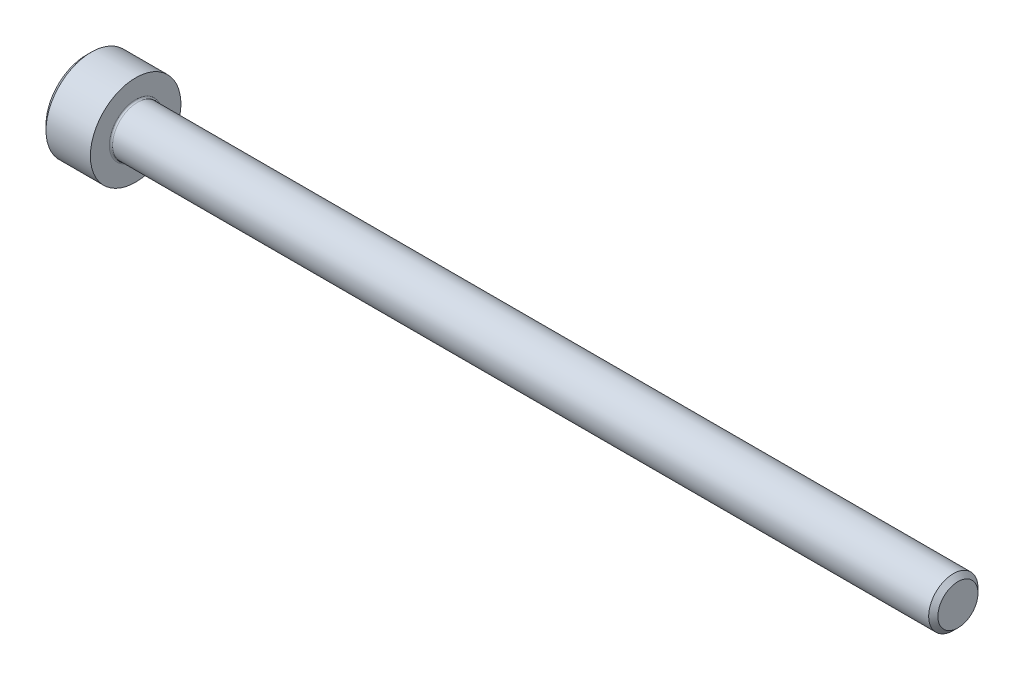
SolidWorks part; units mm, degrees
revolve "Base-Revolve" add sketch "BodySke"
sketch "BodySke" plane through (0, 0, 0) normal (0, 0, 1) x (1, 0, 0)
  line L0 (0, 0) -> (0, 2.45)
  line L1 (0.3, 2.75) -> (3, 2.75)
  line L2 (3, 2.75) -> (3, 1.5)
  line L3 (3, 1.5) -> (52.7195, 1.5)
  line L4 (53, 1.2195) -> (53, 0)
  line L5 (53, 0) -> (0, 0)
  line L6 (-31.75, 0) -> (127, 0) construction
  line L7 (0, 2.45) -> (0.3, 2.75)
  line L8 (53, 1.2195) -> (52.7195, 1.5)
  line L9 (0, -2.45) -> (0.3, -2.75) construction
  line L10 (53, -1.2195) -> (52.7195, -1.5) construction
  line L11 (3.5, 9.525) -> (3.5, 3.175) construction
  line L12 (35, 9.525) -> (35, 3.175) construction
  line L13 (3, 9.525) -> (3, 3.175) construction
  dimension "Diameter" = 3
  dimension "Head_ht" = 3
  dimension "Length" = 50
  dimension "Body_ch_ang" = 45
  dimension "Head_dia" = 5.5
  dimension "Head_ch_ang" = 45
  dimension "Minor_dia" = 2.439
  dimension "Advance" = 0.5
  dimension "Thread_nom" = 18
  dimension "Thread_length" = 50
  dimension "Head_ch_ht" = 0.3
cosmetic thread "ThreadCosmetic" [suppressed]
fillet "Fillet1" radius 0.1 1 edges at (3, 0, 1.5)
ref_plane "Plane1" through (0, 0, 0) normal (0, 0, 1) x (1, 0, 0)
ref_plane "Plane2" through (0, 0, 0) normal (0, 1, 0) x (1, 0, 0)
ref_plane "Plane3" through (0, 0, 0) normal (1, 0, 0) x (0, 0, -1)
sketch "Sketch2" plane through (0, 0, 0) normal (0, 0, 1) x (1, 0, 0)
  line L0 (0, 1.28) -> (1.3, 1.28)
  line L1 (1.3, 1.28) -> (2.039, 0)
  line L2 (-31.75, 0) -> (127, 0) construction
  line L3 (2.039, 0) -> (0, 0)
  line L4 (0, 0) -> (0, 1.28)
  line L5 (0, 2.45) -> (0, -2.45) construction
  line L6 (0, 0) -> (47.625, 0) construction
  line L7 (3, -2.75) -> (3, 2.75) construction
  dimension "D1" = 1.28
  dimension "D2" = 60
revolve "Hex-PreBroach" cut sketch "Sketch2" angle 360 about L6
sketch "Sketch3" plane through (0, 0, 0) normal (-1, 0, 0) x (0, 0.5, 0.866)
  line L0 (0.739, 1.28) -> (-0.739, 1.28)
  line L1 (-0.739, 1.28) -> (-1.478, 0)
  line L2 (0.739, 1.28) -> (1.478, 0)
  line L3 (0.739, -1.28) -> (1.478, 0)
  line L4 (0.739, -1.28) -> (-0.739, -1.28)
  line L5 (-0.739, -1.28) -> (-1.478, 0)
  dimension "D1" = 1.28
  dimension "D2" = 1.28
  dimension "Hex_size" = 2.56
extrude "Hex" cut sketch "Sketch3" against normal blind 1.3
sketch "Sketch4" plane through (0, 0, 0) normal (-1, 0, 0) x (0, 0, 1)
  line L0 (0, 0) -> (1.4605, 0)
  line L1 (0, 0) -> (6.1484, 3.5498) construction
  line L2 (0, 0) -> (0.7302, 1.2648)
  line L3 (1.2009, 0.3267) -> (1.3933, 0.4378)
  line L4 (0.8834, 0.8767) -> (1.0758, 0.9877)
  arc A0 (1.2009, 0.3267) -> (0.8834, 0.8767) centre (0, 0) ccw
  arc A1 (1.4605, 0) -> (1.3933, 0.4378) centre (0, 0) ccw
  arc A2 (0.7302, 1.2648) -> (1.0758, 0.9877) centre (0, 0) cw
  dimension "D1" = 30
  dimension "D2" = 60
  dimension "Spline_p_dim" = 0.635
  dimension "D3" = 0.3175
extrude "Spline" [suppressed] cut sketch "Sketch4" against normal blind 1.3
pattern_circular "CirPattern1" [suppressed] count 6 every 60
sketch "Sketch5" plane through (0, 0, 0) normal (0, 0, 1) x (1, 0, 0)
  line L0 (-31.75, 0) -> (127, 0) construction
  line L2 (0, 2.45) -> (0, -2.45) construction
  circle A0 centre (1.2, 0) radius 0.475
  dimension "Drilled_hole_dia" = 0.95
  dimension "Drilled_hole_loc" = 1.2
extrude "Hole" [suppressed] cut sketch "Sketch5" against normal through all and the other way through all
pattern_circular "Drilled-4" [suppressed] count 2 every 60
pattern_circular "Drilled-6" [suppressed] count 3 every 60
sketch "ThdSchSke" plane through (0, 0, 0) normal (0, 0, 1) x (1, 0, 0)
  line L0 (35, -1.2195) -> (34.8036, -1.5)
  line L1 (35, -1.2195) -> (35.1964, -1.5)
  line L2 (35.1964, -1.5) -> (35.1964, -1.875)
  line L3 (-3.175, 0) -> (5.1513, 0) construction
  line L5 (35.1964, -1.875) -> (34.8036, -1.875)
  line L6 (34.8036, -1.875) -> (34.8036, -1.5)
  line L7 (0, 2.45) -> (0, -2.45) construction
  dimension "Thread_minor" = 2.439
  dimension "Diameter" = 3
revolve "ThreadSchematic" [suppressed] cut sketch "ThdSchSke" angle 360 about L3
pattern_linear "ThdSchPat" [suppressed]
equation "\"D2@Sketch3\" = \"Hex_size@Sketch3\" / 2"
equation "\"D1@Sketch3\" = \"Hex_size@Sketch3\" / 2"
equation "\"D1@Sketch2\" = \"Hex_size@Sketch3\" / 2"
equation "\"D3@Sketch4\" = \"Spline_p_dim@Sketch4\" / 2"
equation "\"Thread_minor@ThreadCosmetic\"  =  \"Minor_dia@BodySke\""
equation "\"D2@CirPattern1\" = 360 / \"Num_teeth@CirPattern1\""
equation "\"Wall_thickness@Sketch2\" = \"Head_ht@BodySke\" - \"Key_eng@Hex\""
equation "\"Thread_length@ThreadCosmetic\" = ((sgn( (\"Length@BodySke\" - \"Advance@BodySke\" ) - \"Thread_nom@BodySke\" )-1)*( (\"Length@BodySke\" - \"Advance@BodySke\" ) - \"Thread_nom@BodySke\" ))/-2+ \"Thread_nom@BodySke\""
equation "\"Thread_minor@ThdSchSke\" = \"Minor_dia@BodySke\""
equation "\"Diameter@ThdSchSke\" = \"Diameter@BodySke\""
equation "\"Overcut@ThdSchSke\" = \"Diameter@BodySke\" * 1.25"
equation "\"Start@ThdSchSke\" = \"Head_ht@BodySke\" + \"Length@BodySke\" - \"Thread_length@ThreadCosmetic\"  '---Non-countersunk---"
equation "\"Num_threads@ThdSchPat\" = int( \"Thread_length@ThreadCosmetic\" / \"Advance@BodySke\" + 0.999 )  + 1"
equation "\"Advance@ThdSchPat\" = \"Thread_length@ThreadCosmetic\" /  (\"Num_threads@ThdSchPat\" - 1) 'relax it"
equation "\"Num_threads@ThdSchPat\" = \"Num_threads@ThdSchPat\" - sgn( \"Num_threads@ThdSchPat\" - 1) '---chamfered tips only---"
